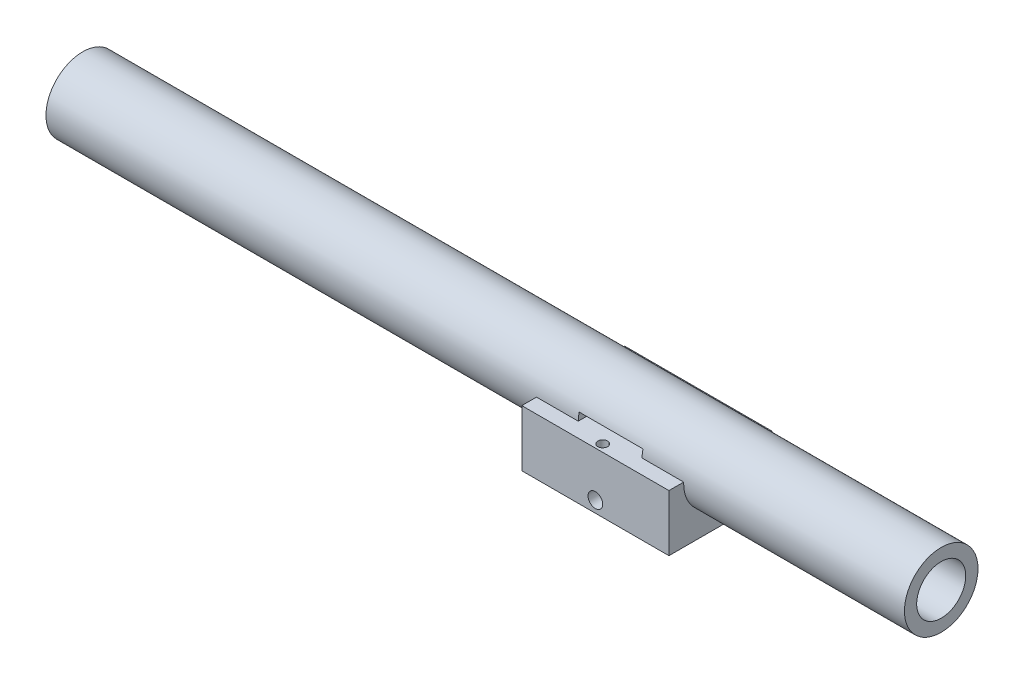
SolidWorks part; units mm, degrees
ref_plane "Front Plane" through (0, 0, 0) normal (0, 0, 1) x (1, 0, 0)
ref_plane "Top Plane" through (0, 0, 0) normal (0, 1, 0) x (1, 0, 0)
ref_plane "Right Plane" through (0, 0, 0) normal (1, 0, 0) x (0, 0, -1)
sketch "Sketch1" plane through (0, 0, 0) normal (1, 0, 0) x (0, 0, -1)
  circle A0 centre (-37.2908, 15.0495) radius 1.905
  circle A1 centre (-37.2908, 15.0495) radius 1.27
extrude "Boss-Extrude1" add sketch "Sketch1" along normal blind 44.45
ref_plane "Plane1" through (0, 0, 39.1958) normal (0, 0, 1) x (1, 0, 0)
sketch "Sketch2" plane through (0, 0, 39.1958) normal (0, 0, 1) x (1, 0, 0)
  line L1 (32.385, 15.1201) -> (33.02, 15.1201)
  line L10 (26.035, 15.1201) -> (31.75, 15.1201)
  line L12 (32.385, 15.1201) -> (31.75, 15.1201)
  line L15 (26.035, 15.1201) -> (25.4, 15.1201)
  line L16 (33.02, 15.1201) -> (33.02, 12.1991)
  line L17 (25.4, 15.1201) -> (25.4, 12.1991)
  line L18 (25.4, 12.1991) -> (33.02, 12.1991)
  line L19 (29.21, 12.1991) -> (27.305, 12.1991)
  line L20 (29.21, 12.1991) -> (31.194, 12.1991)
  dimension "D1" = 2.921
extrude "Boss-Extrude3" add sketch "Sketch2" along normal blind 0.762 and the other way blind 4.572 contours L16 L18 L17 L15 L10 L12 L1
sketch "Sketch4" plane through (0, 0, 0) normal (-1, 0, 0) x (0, 0, 1)
  circle A0 centre (37.2908, 15.0495) radius 1.27
extrude "Cut-Extrude2" cut sketch "Sketch4" against normal blind 46.99
sketch "Sketch5" plane through (0, 0, 39.1958) normal (0, 0, 1) x (1, 0, 0)
  line L0 (44.45, 13.1445) -> (44.45, 16.9545) construction
  line L1 (27.559, 15.5011) -> (30.861, 15.5011)
  line L2 (27.559, 15.5011) -> (27.559, 15.1201)
  line L3 (27.559, 15.1201) -> (30.861, 15.1201)
  line L4 (30.861, 15.5011) -> (30.861, 15.1201)
  line L5 (0, 16.9545) -> (0, 13.1445) construction
  line L7 (25.4, 15.1201) -> (33.02, 15.1201) construction
  dimension "D1" = 0.381
extrude "Cut-Extrude3" cut sketch "Sketch5" against normal blind 1.016
sketch "Sketch6" plane through (0, 0, 39.9578) normal (0, 0, 1) x (1, 0, 0)
  circle A0 centre (29.21, 12.7897) radius 0.381
extrude "Cut-Extrude4" cut sketch "Sketch6" against normal blind 5.588
sketch "Sketch8" plane through (0, 15.1201, 0) normal (0, 1, 0) x (1, 0, 0)
  circle A0 centre (29.21, -39.5768) radius 0.254
extrude "Cut-Extrude5" cut sketch "Sketch8" against normal blind 1.27
